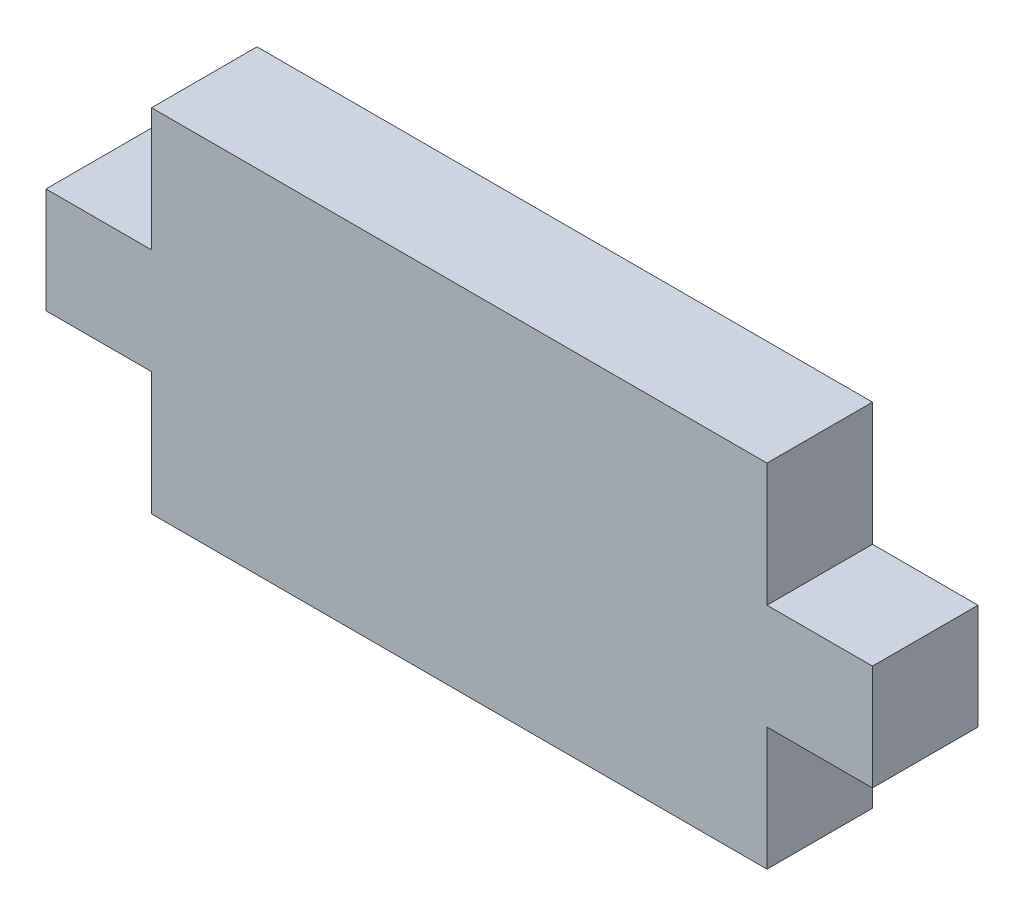
SolidWorks part; units mm, degrees
ref_plane "Спереди" through (0, 0, 0) normal (0, 0, 1) x (1, 0, 0)
ref_plane "Сверху" through (0, 0, 0) normal (0, 1, 0) x (1, 0, 0)
ref_plane "Справа" through (0, 0, 0) normal (1, 0, 0) x (0, 0, -1)
sketch "Эскиз1" plane through (0, 0, 0) normal (0, 0, 1) x (1, 0, 0)
  line L0 (-117.7576, 129.4701) -> (-117.0899, 135.4328) construction
  line L1 (-32.0154, 0) -> (41.5798, 0) construction
  line L2 (0, 23.9777) -> (0, -21.6438) construction
  line L3 (-23.5, -3) -> (-23.5, 3)
  line L4 (-23.5, 3) -> (-17.5, 3)
  line L5 (-17.5, 3) -> (-17.5, 10)
  line L6 (-17.5, 10) -> (17.5, 10)
  line L7 (17.5, 3) -> (17.5, 10)
  line L8 (23.5, 3) -> (17.5, 3)
  line L9 (23.5, -3) -> (23.5, 3)
  line L10 (23.5, -3) -> (17.5, -3)
  line L11 (17.5, -3) -> (17.5, -10)
  line L12 (-17.5, -10) -> (17.5, -10)
  line L13 (-17.5, -3) -> (-17.5, -10)
  line L14 (-23.5, -3) -> (-17.5, -3)
  point P7 (0, -10)
  point P13 (0, 10)
  point P17 (23.5, 0)
  point P22 (-23.5, 0)
  dimension "D2" = 6
  dimension "D3" = 6
  dimension "D4" = 35
  dimension "D1" = 20
extrude "Бобышка-Вытянуть1" add sketch "Эскиз1" along normal blind 6
